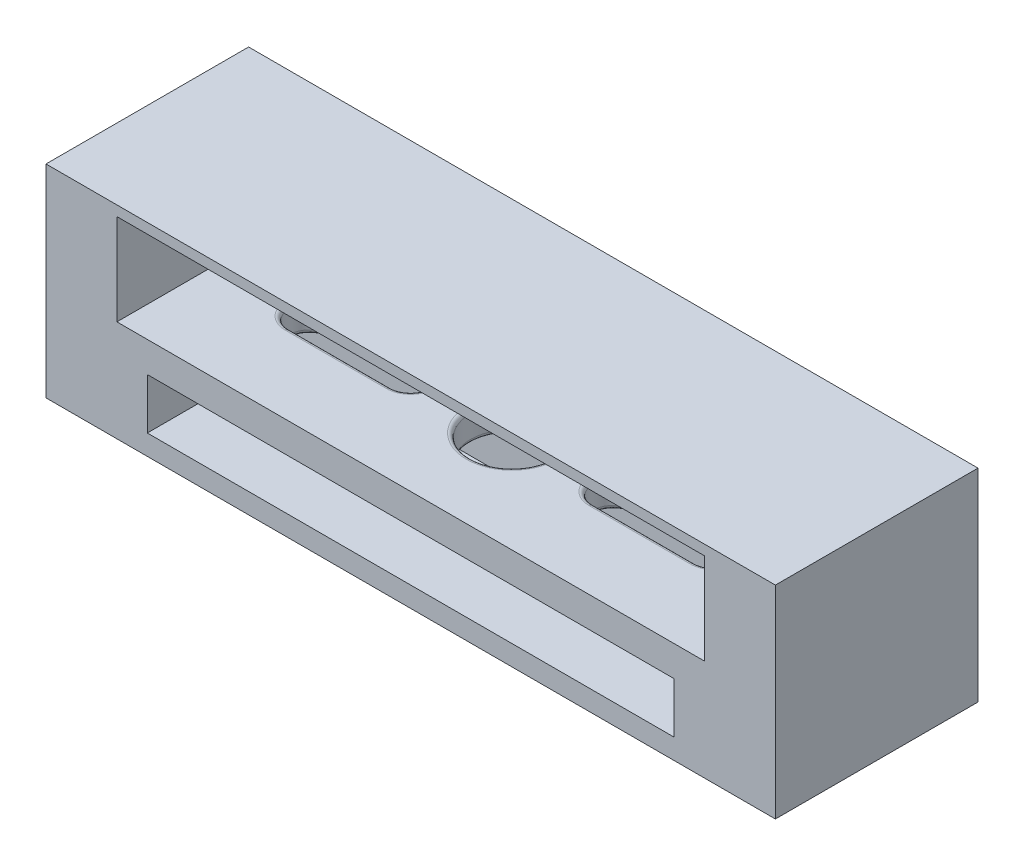
SolidWorks part; units mm, degrees
ref_plane "前视基准面" through (0, 0, 0) normal (0, 0, 1) x (1, 0, 0)
ref_plane "上视基准面" through (0, 0, 0) normal (0, 1, 0) x (1, 0, 0)
ref_plane "右视基准面" through (0, 0, 0) normal (1, 0, 0) x (0, 0, -1)
other "Configuration Table"
sketch "草图1" plane through (0, 0, 0) normal (0, 1, 0) x (1, 0, 0)
  line L1 (0, 0) -> (360, 0)
  line L2 (0, 0) -> (0, -100)
  line L3 (0, -100) -> (360, -100)
  line L4 (360, 0) -> (360, -100)
  dimension "D1" = 360
  dimension "D2" = 100
extrude "凸台-拉伸1" add sketch "草图1" along normal blind 50
sketch "草图2" plane through (0, 50, 0) normal (0, 1, 0) x (1, 0, 0)
  line L0 (0, -50) -> (360, -50) construction
  line L1 (0, 0) -> (0, -100) construction
  line L2 (360, -100) -> (360, 0) construction
  line L3 (180, 0) -> (180, -100) construction
  line L4 (360, 0) -> (0, 0) construction
  line L5 (0, -100) -> (360, -100) construction
  line L6 (80, -50) -> (130, -50) construction
  line L7 (80, -40) -> (130, -40)
  line L8 (80, -60) -> (130, -60)
  line L9 (230, -50) -> (280, -50) construction
  line L10 (230, -40) -> (280, -40)
  line L11 (230, -60) -> (280, -60)
  arc A0 (80, -40) -> (80, -60) centre (80, -50) ccw
  arc A1 (130, -60) -> (130, -40) centre (130, -50) ccw
  arc A2 (230, -40) -> (230, -60) centre (230, -50) ccw
  arc A3 (280, -60) -> (280, -40) centre (280, -50) ccw
  point P12 (180, -50)
  point P15 (105, -50)
  point P20 (255, -50)
  dimension "D3" = 10
  dimension "D1" = 50
  dimension "D2" = 50
  dimension "D4" = 50
extrude "切除-拉伸1" cut sketch "草图2" against normal blind 40
sketch "草图3" plane through (0, 0, 100) normal (0, 0, 1) x (1, 0, 0)
  line L0 (360, 50) -> (360, 0) construction
  line L1 (50, 10) -> (310, 10)
  line L2 (50, 10) -> (50, 35)
  line L3 (50, 35) -> (310, 35)
  line L4 (310, 10) -> (310, 35)
  line L5 (0, 50) -> (0, 0) construction
  line L6 (0, 0) -> (360, 0) construction
  dimension "D1" = 50
  dimension "D2" = 50
  dimension "D3" = 25
  dimension "D4" = 10
extrude "切除-拉伸2" cut sketch "草图3" against normal blind 70
sketch "草图4" plane through (0, 50, 0) normal (0, 1, 0) x (1, 0, 0)
  circle A0 centre (180, -50) radius 20.5
  dimension "D1" = 41
extrude "切除-拉伸3" cut sketch "草图4" against normal blind 20
fillet "圆角4" radius 2 20 edges at (290, 50, 50) (255, 50, 60) (220, 50, 50) (220, 35, 50) (255, 35, 60) (290, 35, 50) (140, 50, 50) (105, 50, 60) (70, 50, 50) (70, 35, 50) (105, 35, 60) (140, 35, 50) (255, 50, 40) (255, 35, 40) (105, 50, 40) (105, 35, 40) (175.5, 32.5, 30) (184.5, 32.5, 30) (180, 35, 70.5) (180, 50, 70.5)
sketch "草图6" plane through (0, 50, 0) normal (0, 1, 0) x (1, 0, 0)
  line L0 (180, 0) -> (180, -100) construction
  line L1 (360, 0) -> (0, 0) construction
  line L2 (0, -100) -> (360, -100) construction
  line L3 (360, -100) -> (325, -100)
  line L4 (0, 0) -> (35, 0)
  line L5 (0, 0) -> (0, -100)
  line L6 (0, -100) -> (35, -100)
  line L7 (35, 0) -> (35, -100)
  line L8 (360, 0) -> (360, -100)
  line L9 (360, 0) -> (325, 0)
  line L10 (325, 0) -> (325, -100)
  circle A0 centre (180, -50) radius 125 construction
  dimension "D1" = 250
  dimension "D2" = 145
extrude "凸台-拉伸2" add sketch "草图6" along normal blind 45
sketch "草图7" plane through (0, 95, 0) normal (0, 1, 0) x (1, 0, 0)
  line L1 (0, 0) -> (360, 0)
  line L2 (0, 0) -> (0, -100)
  line L3 (0, -100) -> (360, -100)
  line L4 (360, 0) -> (360, -100)
extrude "凸台-拉伸3" add sketch "草图7" along normal blind 5
